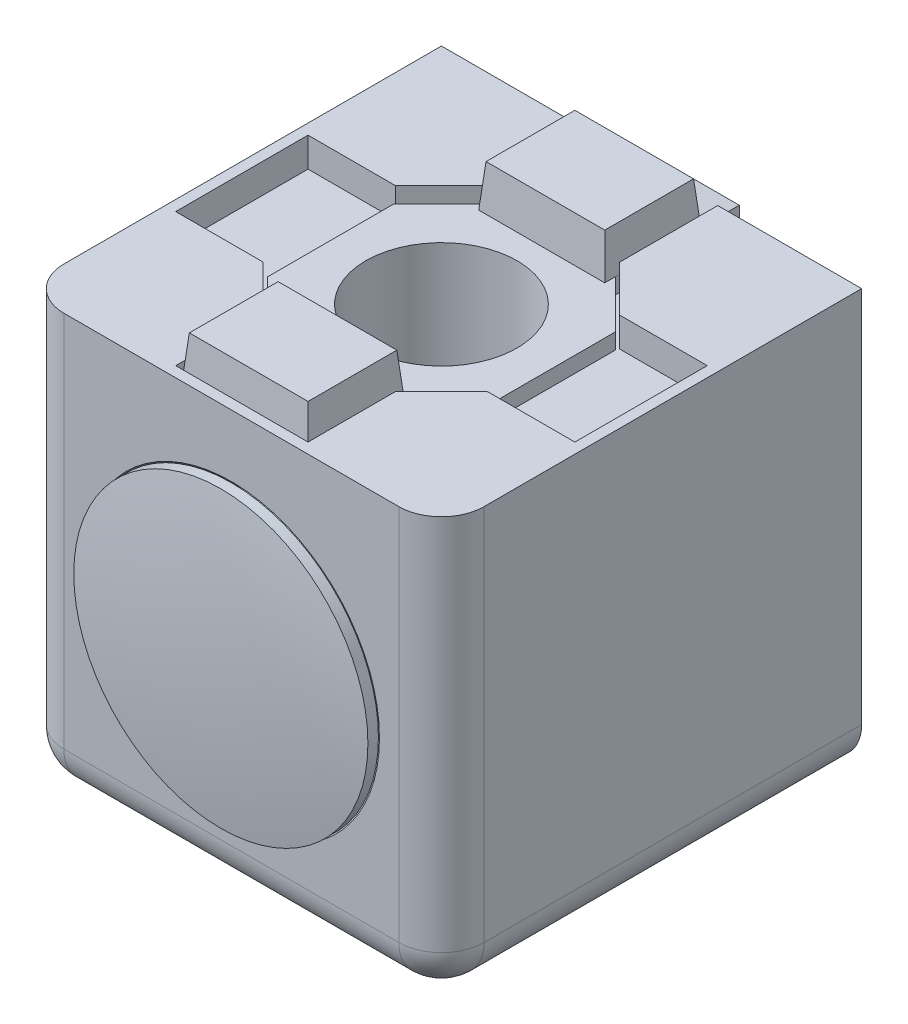
SolidWorks part; units mm, degrees
material "6061 Alloy"
ref_plane "Front Plane" through (0, 0, 0) normal (0, 0, 1) x (1, 0, 0)
ref_plane "Top Plane" through (0, 0, 0) normal (0, 1, 0) x (1, 0, 0)
ref_plane "Right Plane" through (0, 0, 0) normal (1, 0, 0) x (0, 0, -1)
sketch "Sketch1" plane through (0, 0, 0) normal (0, 0, 1) x (1, 0, 0)
  line L0 (-10, -10) -> (10, 10) construction
  line L1 (-10, 10) -> (10, 10)
  line L2 (-10, 10) -> (-10, -10)
  line L3 (-10, -10) -> (10, -10)
  line L4 (10, 10) -> (10, -10)
  dimension "D1" = 20
extrude "Extrude1" add sketch "Sketch1" along normal mid plane 20
sketch "Sketch2" plane through (0, 0, 10) normal (0, 0, 1) x (1, 0, 0)
  circle A0 centre (0, 0) radius 6
  dimension "D1" = 12
extrude "Cut-Extrude1" cut sketch "Sketch2" against normal through all
sketch "Sketch3" plane through (0, 0, 10) normal (0, 0, 1) x (1, 0, 0)
  circle A0 centre (0, 0) radius 7.05
  dimension "D1" = 14.1
extrude "Cut-Extrude2" cut sketch "Sketch3" against normal through all draft 45
sketch "Sketch4" plane through (0, 0, -10) normal (0, 0, -1) x (-1, 0, 0)
  circle A0 centre (0, 0) radius 3.6
  circle A1 centre (0, 0) radius 6 construction
  circle A2 centre (0, 0) radius 6
  dimension "D1" = 7.2
extrude "Extrude2" add sketch "Sketch4" against normal blind 6
sketch "Sketch10" plane through (0, 0, -10) normal (0, 0, -1) x (-1, 0, 0)
  line L0 (-5.3353, 3.15) -> (-3.15, 5.3353)
  line L1 (-3.15, 9.5) -> (3.15, 9.5)
  line L2 (-3.15, 9.5) -> (-3.15, 5.3353)
  line L3 (-3.15, -9.5) -> (3.15, -9.5)
  line L4 (3.15, 9.5) -> (3.15, 5.3353)
  line L5 (-9.5, 3.15) -> (-5.3353, 3.15)
  line L6 (-9.5, 3.15) -> (-9.5, -3.15)
  line L7 (-9.5, -3.15) -> (-5.3353, -3.15)
  line L8 (9.5, 3.15) -> (9.5, -3.15)
  line L9 (3.15, 5.3353) -> (5.3353, 3.15)
  line L10 (5.3353, -3.15) -> (3.15, -5.3353)
  line L11 (-3.15, -5.3353) -> (-5.3353, -3.15)
  line L12 (-10, 0) -> (0, 0) construction
  line L13 (-3.15, -5.3353) -> (-3.15, -9.5)
  line L14 (3.15, -5.3353) -> (3.15, -9.5)
  line L15 (5.3353, -3.15) -> (9.5, -3.15)
  line L16 (5.3353, 3.15) -> (9.5, 3.15)
  line L17 (-10, -10) -> (-10, 10) construction
  line L18 (0, 0) -> (0, 10) construction
  line L19 (-10, 10) -> (10, 10) construction
  line L20 (0, 0) -> (9.5, 0) construction
  line L21 (0, 0) -> (0, -9.5) construction
  dimension "D1" = 6.3
  dimension "D2" = 45
  dimension "D3" = 12
  dimension "D4" = 19
extrude "Cut-Extrude5" cut sketch "Sketch10" against normal blind 1.4
sketch "Sketch13" plane through (0, 0, -8.6) normal (0, 0, -1) x (-1, 0, 0)
  line L16 (5.2731, 3) -> (5.2731, -3)
  line L17 (-5.2731, 3) -> (-5.2731, -3)
  line L32 (-3, 9.35) -> (-3, 5.2731)
  line L33 (-3, 5.2731) -> (-5.2731, 3)
  line L34 (-5.2731, 3) -> (-9.35, 3)
  line L35 (-9.35, 3) -> (-9.35, -3)
  line L36 (-9.35, -3) -> (-5.2731, -3)
  line L37 (-5.2731, -3) -> (-3, -5.2731)
  line L38 (-3, -5.2731) -> (-3, -9.35)
  line L39 (-3, -9.35) -> (3, -9.35)
  line L40 (3, -9.35) -> (3, -5.2731)
  line L41 (3, -5.2731) -> (5.2731, -3)
  line L42 (5.2731, -3) -> (9.35, -3)
  line L43 (9.35, -3) -> (9.35, 3)
  line L44 (9.35, 3) -> (5.2731, 3)
  line L45 (5.2731, 3) -> (3, 5.2731)
  line L46 (3, 5.2731) -> (3, 9.35)
  line L47 (3, 9.35) -> (-3, 9.35)
  line L48 (-3, 9.35) -> (-3, 5.2731)
  line L49 (-3, 5.2731) -> (-5.2731, 3)
  line L53 (-5.2731, -3) -> (-3, -5.2731)
  line L54 (-3, -5.2731) -> (-3, -9.35)
  line L55 (-3, -9.35) -> (3, -9.35)
  line L56 (3, -9.35) -> (3, -5.2731)
  line L57 (3, -5.2731) -> (5.2731, -3)
  line L61 (5.2731, 3) -> (3, 5.2731)
  line L62 (3, 5.2731) -> (3, 9.35)
  line L63 (3, 9.35) -> (-3, 9.35)
  circle A0 centre (0, 0) radius 3.6 construction
  circle A1 centre (0, 0) radius 3.6
  dimension "D1" = 0.15
extrude "Extrude3" add sketch "Sketch13" along normal blind 0.75
sketch "Sketch14" plane through (0, 0, -9.35) normal (0, 0, -1) x (-1, 0, 0)
  line L0 (3, 5.2731) -> (3, 9.35) construction
  line L1 (-3, 9.35) -> (3, 9.35)
  line L2 (-3, 9.35) -> (-3, 4.7731)
  line L3 (-3, 4.7731) -> (3, 4.7731)
  line L4 (3, 9.35) -> (3, 4.7731)
  line L5 (-3, -9.35) -> (3, -9.35)
  line L6 (-3, -9.35) -> (-3, -4.7731)
  line L7 (-3, -4.7731) -> (3, -4.7731)
  line L8 (3, -9.35) -> (3, -4.7731)
  dimension "D1" = 0.5
  dimension "D2" = 0.5
extrude "Extrude4" add sketch "Sketch14" along normal blind 2 draft 5
sketch "Sketch7" plane through (0, 0, 0) normal (0, 1, 0) x (1, 0, 0)
  line L0 (0, 0) -> (-10, 0) construction
  line L1 (-10, -10) -> (-10, 10) construction
ref_axis "Axis1" through (-10, 0, 0) along (1, 0, 0)
fillet "Fillet2" radius 2.032 5 edges at (0, -10, 10) (-10, -10, 0) (-10, 0, 10) (10, -10, 0) (10, 0, 10)
sketch "Sketch9" plane through (0, 0, 0) normal (1, 0, 0) x (0, 0, -1)
  line L0 (-10, 7) -> (-10, 6)
  line L1 (-10, 6) -> (-7, 6)
  line L2 (-7, 6) -> (-7, 5.5)
  line L3 (-7, 5.5) -> (-10, 5.5)
  line L4 (-10, 5.5) -> (-10, 0)
  line L5 (-10, 0) -> (-11, 0)
  line L6 (-10, 7) -> (-10.5, 7)
  line L7 (-10, 10) -> (-10, -7.968) construction
  line L8 (-10, 0) -> (0, 0) construction
  arc A0 (-10.5, 7) -> (-11, 0) centre (38.25, 0) ccw
  dimension "D1" = 0.5
  dimension "D2" = 3
  dimension "D3" = 1
  dimension "D4" = 1
revolve "Revolve1" add sketch "Sketch9" angle 360 about L8
pattern_circular "CirPattern1" count 2 over 90 about axis through (0, 0, 0) along (1, 0, 0) of "Cut-Extrude1", "Cut-Extrude2", "Extrude2", "Revolve1", "Cut-Extrude5", "Extrude3", "Extrude4"
ref_plane "Plane1" through (0, 0, 0) normal (0, 0.7071, 0.7071) x (1, 0, 0)
sketch "Sketch12" plane through (0, 9.5, 0) normal (0, -1, 0) x (1, 0, 0)
  line L4 (3.15, -10) -> (3.15, -9.5)
  line L5 (3.15, -9.5) -> (-3.15, -9.5)
  line L6 (-3.15, -9.5) -> (-3.15, -10)
  line L7 (-3.15, -10) -> (3.15, -10)
  line L8 (3.15, -10) -> (3.15, -9.5)
  line L9 (3.15, -9.5) -> (-3.15, -9.5)
  line L10 (-3.15, -9.5) -> (-3.15, -10)
  line L11 (-3.15, -10) -> (3.15, -10)
  dimension "D1" = 0
extrude "Cut-Extrude6" cut sketch "Sketch12" against normal through all
